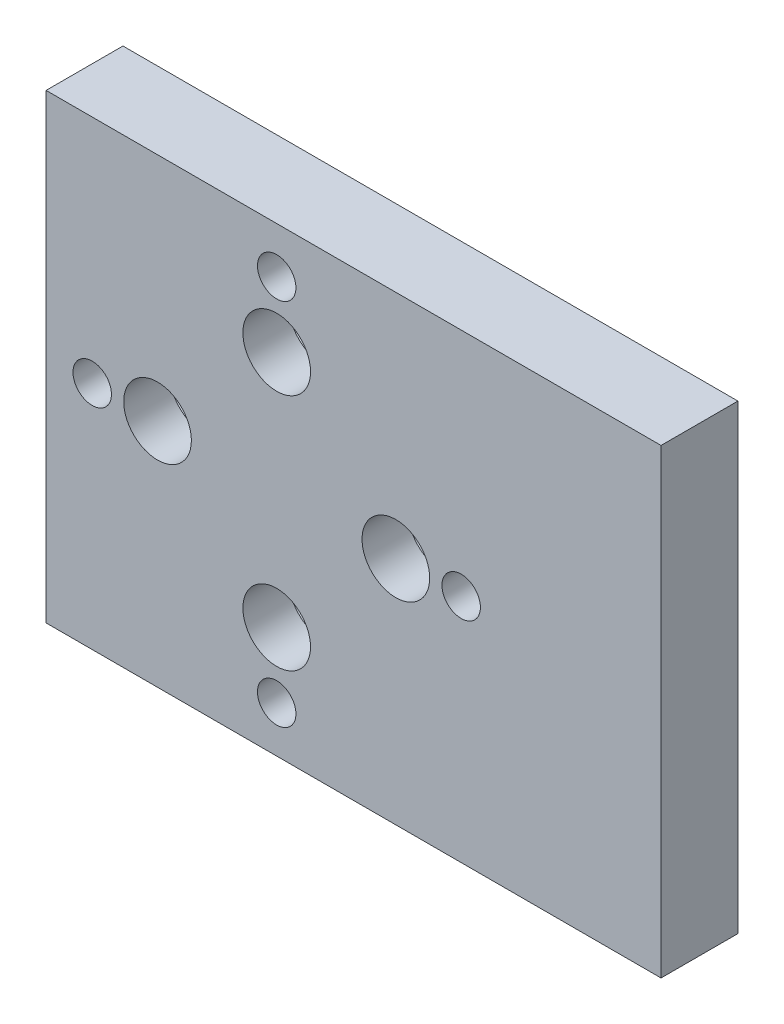
SolidWorks part; units mm, degrees
ref_plane "정면" through (0, 0, 0) normal (0, 0, 1) x (1, 0, 0)
ref_plane "윗면" through (0, 0, 0) normal (0, 1, 0) x (1, 0, 0)
ref_plane "우측면" through (0, 0, 0) normal (1, 0, 0) x (0, 0, -1)
sketch "스케치1" plane through (0, 0, 0) normal (0, 0, 1) x (1, 0, 0)
  line L1 (-40, 30) -> (40, 30)
  line L2 (-40, 30) -> (-40, -30)
  line L3 (-40, -30) -> (40, -30)
  line L4 (40, 30) -> (40, -30)
  line L5 (0, -30) -> (0, 30) construction
  line L6 (-40, 0) -> (40, 0) construction
  point P0 (0, 0)
  dimension "D1" = 60
  dimension "D2" = 80
extrude "보스-돌출1" add sketch "스케치1" along normal blind 10
sketch "스케치2" plane through (0, 0, 10) normal (0, 0, 1) x (1, 0, 0)
  line L0 (0, 30) -> (0, -30) construction
  line L1 (40, 30) -> (-40, 30) construction
  line L2 (-40, -30) -> (40, -30) construction
  line L3 (0, -30) -> (-40, 0) construction
  line L4 (-40, 30) -> (-40, -30) construction
  line L5 (-40, 0) -> (40, 0) construction
  line L6 (40, -30) -> (40, 30) construction
  line L7 (40, 0) -> (0, 30) construction
  line L8 (0, 30) -> (-40, 0) construction
  line L9 (-10, 15.5) -> (-10, -15.5) construction
  line L10 (-10, -15.5) -> (-25.5, 0) construction
  line L11 (-25.5, 0) -> (5.5, 0) construction
  circle A0 centre (-10, 0) radius 15.5
  circle A1 centre (-10, 0) radius 24
  point P6 (-10, 0)
  point P19 (-34, 0)
  point P20 (-10, 24)
  point P22 (-10, -24)
  point P23 (14, 0)
  dimension "D1" = 30
hole_wizard "M5 탭을 위한 탭 드릴1" positions "3D스케치1" profile "스케치4" hole size "M5" standard "KS" end condition through all
sketch3d "3D스케치1"
  point P0 (-25.5, 0, 10)
  point P3 (-10, -15.5, 10)
  point P6 (5.5, 0, 10)
  point P9 (-10, 15.5, 10)
sketch "스케치4" plane through (-25.5, 0, 10) normal (1, 0, 0) x (0, -1, 0)
  line L0 (0, 0) -> (0, 10)
  line L1 (0, 10) -> (2.1, 10)
  line L2 (2.1, 10) -> (2.1, 0)
  line L5 (2.1, 0) -> (0, 0)
  line L11 (0, -6.35) -> (0, 107.95) construction
  dimension "관통 구멍 지름" = 4.2
  dimension "관통 구멍 깊이" = 10
hole_wizard "Ø8.8 (8.8) 지름 구멍1" positions "3D스케치3" profile "스케치6" hole size "Ø8.8" standard "KS"
sketch3d "3D스케치3"
  point P0 (-25.5, 0, 10)
  point P4 (-10, 15.5, 10)
  point P7 (5.5, 0, 10)
  point P10 (-10, -15.5, 10)
sketch "스케치6" plane through (-25.5, 0, 10) normal (1, 0, 0) x (0, -1, 0)
  line L0 (0, 0) -> (0, 8.6438)
  line L1 (0, 8.6438) -> (4.4, 6)
  line L2 (4.4, 6) -> (4.4, 0)
  line L5 (4.4, 0) -> (0, 0)
  line L10 (0, 8.6438) -> (-4.4, 6) construction
  line L11 (0, -6.35) -> (0, 107.95) construction
  dimension "구멍 지름" = 8.8
  dimension "구멍 깊이" = 6
  dimension "드릴 각도" = 118
ref_plane "평면1" through (0, 0, 0) normal (0, 0, -1) x (-1, 0, 0)
sketch "스케치9" plane through (0, 0, 0) normal (0, 0, -1) x (-1, 0, 0)
  line L0 (-40, 0) -> (40, 0) construction
  line L1 (40, 0) -> (0, 30) construction
  line L2 (-40, 30) -> (40, 30) construction
  line L3 (0, 30) -> (0, -30) construction
  line L4 (40, -30) -> (-40, -30) construction
  line L5 (0, -30) -> (-40, 0) construction
  line L6 (-40, 0) -> (0, 30) construction
hole_wizard "M6 탭을 위한 탭 드릴1" positions "3D스케치4" profile "스케치10" hole size "M6" standard "KS"
sketch3d "3D스케치4"
  point P0 (-10, 24, 10)
  point P3 (-34, 0, 10)
  point P6 (-10, -24, 10)
  point P9 (14, 0, 10)
sketch "스케치10" plane through (-10, 24, 10) normal (1, 0, 0) x (0, -1, 0)
  line L0 (0, 0) -> (0, 6.5022)
  line L1 (0, 6.5022) -> (2.5, 5)
  line L2 (2.5, 5) -> (2.5, 0)
  line L5 (2.5, 0) -> (0, 0)
  line L10 (0, 6.5022) -> (-2.5, 5) construction
  line L11 (0, -6.35) -> (0, 107.95) construction
  dimension "구멍 지름" = 5
  dimension "구멍 깊이" = 5
  dimension "드릴 각도" = 118
